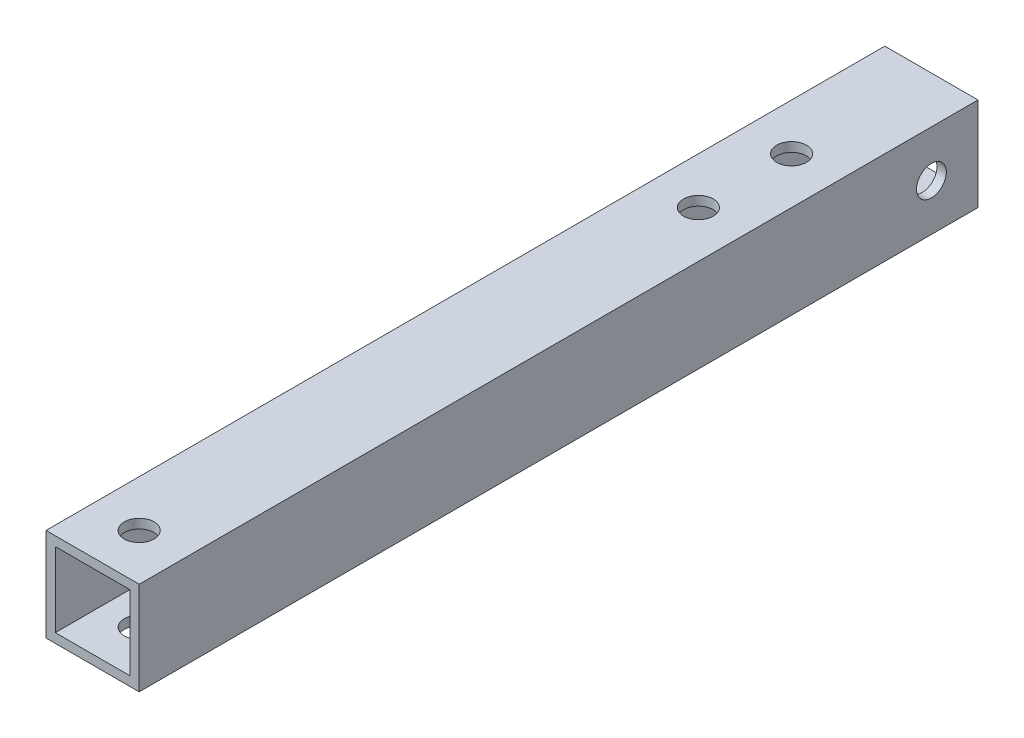
SolidWorks part; units mm, degrees
ref_plane "Front Plane" through (0, 0, 0) normal (0, 0, 1) x (1, 0, 0)
ref_plane "Top Plane" through (0, 0, 0) normal (0, 1, 0) x (1, 0, 0)
ref_plane "Right Plane" through (0, 0, 0) normal (1, 0, 0) x (0, 0, -1)
sketch "ｽｹｯﾁ1" plane through (0, 0, 0) normal (0, 0, 1) x (1, 0, 0)
  line L1 (5, -5) -> (-5, -5)
  line L2 (5, -5) -> (5, 5)
  line L3 (5, 5) -> (-5, 5)
  line L4 (-5, -5) -> (-5, 5)
  line L5 (5, -5) -> (-5, 5) construction
  line L6 (5, 5) -> (-5, -5) construction
  line L7 (4, -4) -> (-4, -4)
  line L8 (4, -4) -> (4, 4)
  line L9 (4, 4) -> (-4, 4)
  line L10 (-4, -4) -> (-4, 4)
  line L11 (4, -4) -> (-4, 4) construction
  line L12 (4, 4) -> (-4, -4) construction
  point P0 (0, 0)
  point P6 (0, 0)
  dimension "D1" = 10
  dimension "D2" = 10
  dimension "D3" = 1
extrude "ﾎﾞｽ - 押し出し1" add sketch "ｽｹｯﾁ1" along normal blind 90
sketch "ｽｹｯﾁ2" plane through (0, 5, 0) normal (0, 1, 0) x (1, 0, 0)
  line L0 (5, 0) -> (-5, 0) construction
  line L1 (5, -90) -> (5, 0) construction
  circle A0 centre (0, -15) radius 1.6
  circle A1 centre (0, -85) radius 1.6
  circle A2 centre (0, -25) radius 1.6
  dimension "D1" = 3.2
  dimension "D2" = 3.2
  dimension "D3" = 3.2
  dimension "D4" = 15
  dimension "D5" = 10
  dimension "D6" = 60
  dimension "D7" = 5
  dimension "D8" = 5
  dimension "D9" = 5
extrude "ｶｯﾄ - 押し出し1" cut sketch "ｽｹｯﾁ2" against normal through all
sketch "ｽｹｯﾁ3" plane through (5, 0, 0) normal (1, 0, 0) x (0, 0, -1)
  line L0 (-90, 5) -> (0, 5) construction
  line L2 (0, -5) -> (0, 5) construction
  circle A0 centre (-5, 0) radius 1.6
  dimension "D1" = 3.2
  dimension "D3" = 5
  dimension "D2" = 5
extrude "ｶｯﾄ - 押し出し2" cut sketch "ｽｹｯﾁ3" against normal blind 60
